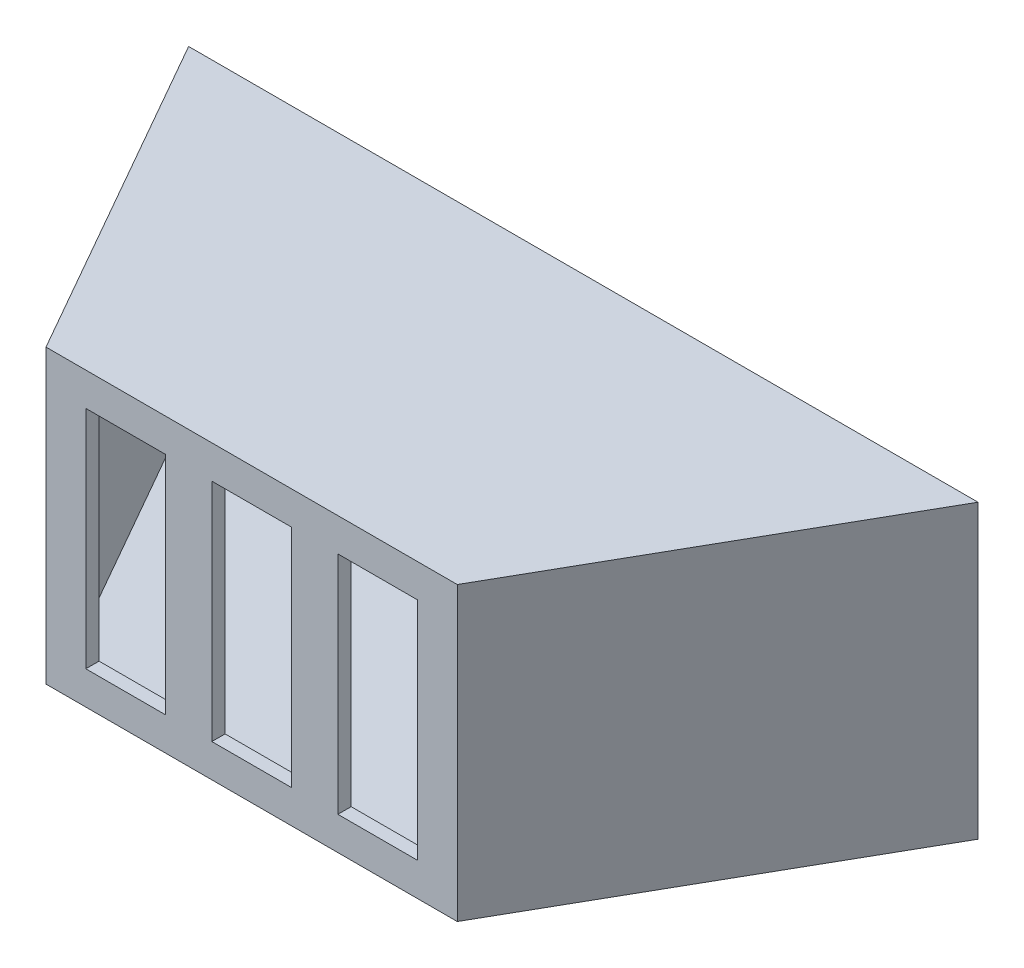
SolidWorks part; units mm, degrees
ref_plane "Plano frontal" through (0, 0, 0) normal (0, 0, 1) x (1, 0, 0)
ref_plane "Plano superior" through (0, 0, 0) normal (0, 1, 0) x (1, 0, 0)
ref_plane "Plano direito" through (0, 0, 0) normal (1, 0, 0) x (0, 0, -1)
sketch "Esboço1" plane through (0, 0, 0) normal (0, 1, 0) x (1, 0, 0)
  line L0 (-59.5, 45.3236) -> (-31, -4.6764)
  line L1 (-31, -4.6764) -> (31, -4.6764)
  line L2 (31, -4.6764) -> (59.5, 45.3236)
  line L3 (59.5, 45.3236) -> (-59.5, 45.3236)
  dimension "D1" = 119
  dimension "D2" = 62
  dimension "D3" = 50
  dimension "D4" = 28.5
  dimension "D5" = 31
extrude "Extrusão1" add sketch "Esboço1" along normal blind 44
shell "Casca1" thickness 2
sketch "Esboço4" plane through (0, 42, 0) normal (0, -1, 0) x (1, 0, 0)
  line L0 (-57.1979, -45.3236) -> (-42.1979, -45.3236)
  line L1 (59.5, -45.3236) -> (-59.5, -45.3236) construction
  line L2 (-42.1979, -45.3236) -> (-42.1979, -42.3236)
  line L3 (-42.1979, -42.3236) -> (-55.4879, -42.3236)
  line L4 (-55.4879, -42.3236) -> (-57.1979, -45.3236)
  line L5 (-59.5, -45.3236) -> (-31, 4.6764) construction
  dimension "D1" = 2
  dimension "D2" = 15
  dimension "D3" = 3
extrude "Extrusão2" add sketch "Esboço4" along normal up to surface (40 mm away) up to face at (0, 2, -21.3236)
mirror "Espelhar1" about plane through (0, 0, 0) normal (1, 0, 0) of "Extrusão2"
sketch "Esboço5" plane through (0, 0, -42.3236) normal (0, 0, 1) x (1, 0, 0)
  line L0 (59.5, 44) -> (-59.5, 44) construction
  line L1 (-59.5, 44) -> (-59.5, 0) construction
  circle A0 centre (-49.5, 34) radius 5.25
  dimension "D1" = 10.5
  dimension "D2" = 10
  dimension "D3" = 10
sketch "Esboço6" plane through (0, 0, -42.3236) normal (0, 0, 1) x (1, 0, 0)
  line L0 (59.5, 0) -> (-59.5, 0) construction
  line L1 (-59.5, 44) -> (-59.5, 0) construction
  circle A0 centre (-49.5, 10) radius 5.25
  dimension "D1" = 10
  dimension "D3" = 10.5
  dimension "D2" = 10
extrude "Extrusão3" cut sketch "Esboço6" against normal blind 2
extrude "Extrusão4" cut sketch "Esboço5" against normal blind 2
mirror "Espelhar2" about plane through (0, 0, 0) normal (1, 0, 0) of "Extrusão3", "Extrusão4"
sketch "Esboço7" plane through (0, 0, 4.6764) normal (0, 0, 1) x (1, 0, 0)
  line L0 (-31, 44) -> (31, 44) construction
  line L1 (-6, 39) -> (6, 39)
  line L2 (-6, 39) -> (-6, 5)
  line L3 (-6, 5) -> (6, 5)
  line L4 (6, 39) -> (6, 5)
  line L5 (13, 39) -> (25, 39)
  line L6 (13, 39) -> (13, 5)
  line L7 (13, 5) -> (25, 5)
  line L8 (25, 39) -> (25, 5)
  line L9 (-25, 39) -> (-13, 39)
  line L10 (-25, 39) -> (-25, 5)
  line L11 (-25, 5) -> (-13, 5)
  line L12 (-13, 39) -> (-13, 5)
  line L13 (-31, 0) -> (31, 0) construction
  line L14 (-31, 44) -> (-31, 0) construction
  dimension "D1" = 5
  dimension "D2" = 5
  dimension "D3" = 5
  dimension "D4" = 5
  dimension "D5" = 12
  dimension "D6" = 5
  dimension "D7" = 5
  dimension "D8" = 12
  dimension "D9" = 12
  dimension "D10" = 7
  dimension "D11" = 7
  dimension "D12" = 6
extrude "Extrusão5" cut sketch "Esboço7" against normal blind 2
